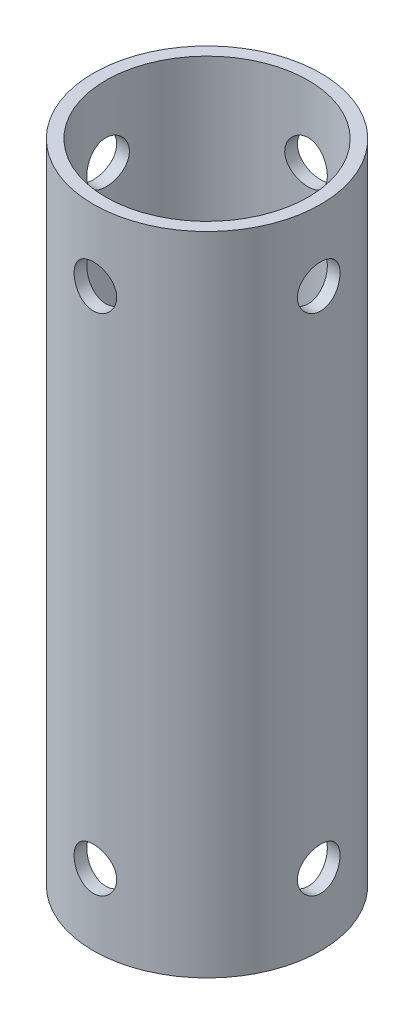
SolidWorks part; units mm, degrees
ref_plane "Front Plane" through (0, 0, 0) normal (0, 0, 1) x (1, 0, 0)
ref_plane "Top Plane" through (0, 0, 0) normal (0, 1, 0) x (1, 0, 0)
ref_plane "Right Plane" through (0, 0, 0) normal (1, 0, 0) x (0, 0, -1)
sketch "Sketch1" plane through (0, 0, 0) normal (0, 1, 0) x (1, 0, 0)
  circle A0 centre (0, 0) radius 14.25
  circle A1 centre (0, 0) radius 16
  dimension "D1" = 28.5
  dimension "D2" = 32
extrude "Boss-Extrude1" add sketch "Sketch1" along normal blind 91
ref_plane "Plane1" through (0, 0, -16) normal (0, 0, -1) x (-1, 0, 0)
sketch "Sketch2" plane through (0, 0, -16) normal (0, 0, -1) x (-1, 0, 0)
  line L0 (0, 0) -> (0, 91) construction
  line L1 (16, 91) -> (-16, 91) construction
  line L2 (-16, 0) -> (16, 0) construction
  line L4 (14.25, 91) -> (-14.25, 91) construction
  circle A0 centre (0, 10) radius 3
  circle A1 centre (0, 81) radius 3
  dimension "D2" = 6
  dimension "D3" = 6
  dimension "D1" = 10
  dimension "D4" = 10
extrude "Cut-Extrude1" cut sketch "Sketch2" against normal blind 10
ref_axis "Axis1" through (0, 91, 0) along (0, -1, 0)
pattern_circular "CirPattern1" count 4 over 360 about axis through (0, 91, 0) along (0, -1, 0) of "Cut-Extrude1"
